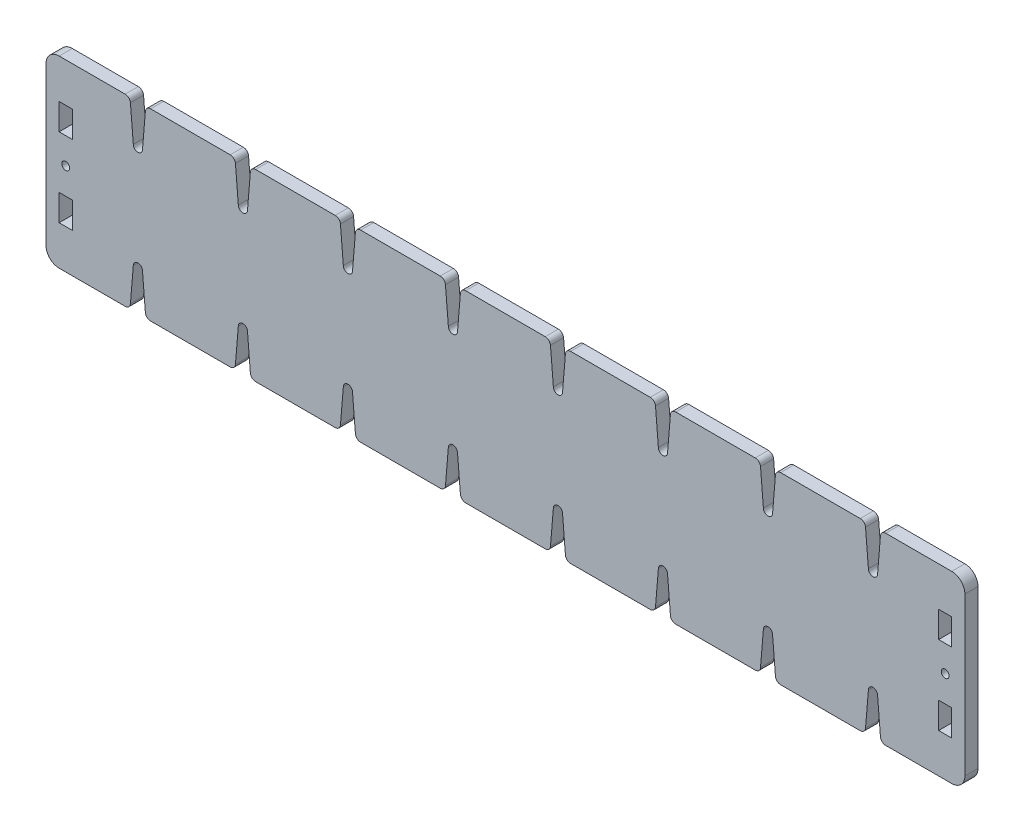
SolidWorks part; units mm, degrees
ref_plane "Front Plane" through (0, 0, 0) normal (0, 0, 1) x (1, 0, 0)
ref_plane "Top Plane" through (0, 0, 0) normal (0, 1, 0) x (1, 0, 0)
ref_plane "Right Plane" through (0, 0, 0) normal (1, 0, 0) x (0, 0, -1)
sketch "Sketch1" plane through (0, 0, 0) normal (0, 0, 1) x (1, 0, 0)
  line L0 (-90.218, 10) -> (299.3045, 10) construction
  line L1 (-85.8133, 35) -> (264.1867, 35)
  line L2 (-85.8133, 35) -> (-85.8133, -35)
  line L3 (-85.8133, -35) -> (264.1867, -35)
  line L4 (264.1867, 35) -> (264.1867, -35)
  line L5 (-80.8133, -10) -> (-75.8133, -10)
  line L6 (-91.3268, 0) -> (299.3045, 0) construction
  line L7 (-80.8133, 20) -> (-75.8133, 20)
  line L8 (-80.8133, 20) -> (-80.8133, 10)
  line L9 (-80.8133, 10) -> (-75.8133, 10)
  line L10 (-75.8133, 20) -> (-75.8133, 10)
  line L11 (-75.8133, -20) -> (-75.8133, -10)
  line L12 (-80.8133, -20) -> (-75.8133, -20)
  line L13 (-80.8133, -20) -> (-80.8133, -10)
  line L14 (89.1867, 30.0157) -> (89.1867, -45.8134) construction
  line L15 (-78.3133, 24.0051) -> (-78.3133, -32.23) construction
  line L16 (259.1867, -20) -> (259.1867, -10)
  line L17 (259.1867, -20) -> (254.1867, -20)
  line L18 (254.1867, -20) -> (254.1867, -10)
  line L19 (259.1867, -10) -> (254.1867, -10)
  line L20 (259.1867, 10) -> (254.1867, 10)
  line L21 (254.1867, 20) -> (254.1867, 10)
  line L22 (259.1867, 20) -> (254.1867, 20)
  line L23 (259.1867, 20) -> (259.1867, 10)
  circle A31 centre (-78.3133, 0) radius 1.5
  circle A32 centre (256.6867, 0) radius 1.5
  point P6 (89.1867, -35)
  point P13 (-85.8133, 0)
  point P82 (-78.3133, 20)
  dimension "D1" = 70
  dimension "D2" = 350
  dimension "D3" = 20
  dimension "D4" = 10
  dimension "D7" = 5
  dimension "D8" = 5
extrude "Boss-Extrude1" add sketch "Sketch1" along normal blind 5
sketch "Sketch2" plane through (0, 0, 5) normal (0, 0, 1) x (1, 0, 0)
  line L0 (-50.8133, 26.1544) -> (-50.8133, -32.4929) construction
  line L1 (-85.8133, 35) -> (-85.8133, -35) construction
  line L2 (264.1867, 35) -> (-85.8133, 35) construction
  line L3 (-53.8133, 35) -> (-47.8133, 35)
  line L4 (-53.8133, 35) -> (-52.5633, 20)
  line L6 (-47.8133, 35) -> (-49.0633, 20)
  line L7 (-86.9763, 0) -> (351.4175, 0) construction
  line L8 (-13.8133, 35) -> (-7.8133, 35)
  line L9 (-13.8133, 35) -> (-12.5633, 20)
  line L10 (-7.8133, 35) -> (-9.0633, 20)
  line L11 (26.1867, 35) -> (32.1867, 35)
  line L12 (26.1867, 35) -> (27.4367, 20)
  line L13 (32.1867, 35) -> (30.9367, 20)
  line L14 (66.1867, 35) -> (72.1867, 35)
  line L15 (66.1867, 35) -> (67.4367, 20)
  line L16 (72.1867, 35) -> (70.9367, 20)
  line L17 (106.1867, 35) -> (112.1867, 35)
  line L18 (106.1867, 35) -> (107.4367, 20)
  line L19 (112.1867, 35) -> (110.9367, 20)
  line L20 (146.1867, 35) -> (152.1867, 35)
  line L21 (146.1867, 35) -> (147.4367, 20)
  line L22 (152.1867, 35) -> (150.9367, 20)
  line L23 (186.1867, 35) -> (192.1867, 35)
  line L24 (186.1867, 35) -> (187.4367, 20)
  line L25 (192.1867, 35) -> (190.9367, 20)
  line L26 (226.1867, 35) -> (232.1867, 35)
  line L27 (226.1867, 35) -> (227.4367, 20)
  line L28 (232.1867, 35) -> (230.9367, 20)
  line L71 (232.1867, -35) -> (230.9367, -20)
  line L72 (226.1867, -35) -> (227.4367, -20)
  line L73 (226.1867, -35) -> (232.1867, -35)
  line L74 (192.1867, -35) -> (190.9367, -20)
  line L75 (186.1867, -35) -> (187.4367, -20)
  line L76 (186.1867, -35) -> (192.1867, -35)
  line L77 (152.1867, -35) -> (150.9367, -20)
  line L78 (146.1867, -35) -> (147.4367, -20)
  line L79 (146.1867, -35) -> (152.1867, -35)
  line L80 (112.1867, -35) -> (110.9367, -20)
  line L81 (106.1867, -35) -> (107.4367, -20)
  line L82 (106.1867, -35) -> (112.1867, -35)
  line L83 (72.1867, -35) -> (70.9367, -20)
  line L84 (66.1867, -35) -> (67.4367, -20)
  line L85 (66.1867, -35) -> (72.1867, -35)
  line L86 (32.1867, -35) -> (30.9367, -20)
  line L87 (26.1867, -35) -> (27.4367, -20)
  line L88 (26.1867, -35) -> (32.1867, -35)
  line L89 (-7.8133, -35) -> (-9.0633, -20)
  line L90 (-13.8133, -35) -> (-12.5633, -20)
  line L91 (-13.8133, -35) -> (-7.8133, -35)
  line L92 (-47.8133, -35) -> (-49.0633, -20)
  line L93 (-53.8133, -35) -> (-52.5633, -20)
  line L94 (-53.8133, -35) -> (-47.8133, -35)
  line L95 (-54.6736, 20) -> (-41.4603, 20) construction
  line L99 (264.1867, 35) -> (-85.8133, 35) construction
  arc A0 (-52.5633, 20) -> (-49.0633, 20) centre (-50.8133, 20) ccw
  arc A1 (-12.5633, 20) -> (-9.0633, 20) centre (-10.8133, 20) ccw
  arc A2 (27.4367, 20) -> (30.9367, 20) centre (29.1867, 20) ccw
  arc A3 (67.4367, 20) -> (70.9367, 20) centre (69.1867, 20) ccw
  arc A4 (107.4367, 20) -> (110.9367, 20) centre (109.1867, 20) ccw
  arc A5 (147.4367, 20) -> (150.9367, 20) centre (149.1867, 20) ccw
  arc A6 (187.4367, 20) -> (190.9367, 20) centre (189.1867, 20) ccw
  arc A7 (227.4367, 20) -> (230.9367, 20) centre (229.1867, 20) ccw
  arc A22 (227.4367, -20) -> (230.9367, -20) centre (229.1867, -20) cw
  arc A23 (187.4367, -20) -> (190.9367, -20) centre (189.1867, -20) cw
  arc A24 (147.4367, -20) -> (150.9367, -20) centre (149.1867, -20) cw
  arc A25 (107.4367, -20) -> (110.9367, -20) centre (109.1867, -20) cw
  arc A26 (67.4367, -20) -> (70.9367, -20) centre (69.1867, -20) cw
  arc A27 (27.4367, -20) -> (30.9367, -20) centre (29.1867, -20) cw
  arc A28 (-12.5633, -20) -> (-9.0633, -20) centre (-10.8133, -20) cw
  arc A29 (-52.5633, -20) -> (-49.0633, -20) centre (-50.8133, -20) cw
  circle A31 centre (-50.8133, 20) radius 17.5 construction
  circle A32 centre (-10.8133, 20) radius 17.5 construction
  circle A33 centre (29.1867, 20) radius 17.5 construction
  circle A34 centre (69.1867, 20) radius 17.5 construction
  circle A35 centre (109.1867, 20) radius 17.5 construction
  circle A36 centre (149.1867, 20) radius 17.5 construction
  circle A37 centre (189.1867, 20) radius 17.5 construction
  circle A38 centre (229.1867, 20) radius 17.5 construction
  point P10 (-50.8133, 35)
  point P23 (0, 0)
  dimension "D1" = 35
  dimension "D2" = 6
  dimension "D3" = 8
  dimension "D4" = 3.5
  dimension "D6" = 15
extrude "Cut-Extrude1" cut sketch "Sketch2" against normal blind 5
fillet "Fillet1" radius 2 32 edges at (-47.8133, -35, 2.5) (-53.8133, -35, 2.5) (-7.8133, -35, 2.5) (-13.8133, -35, 2.5) (32.1867, -35, 2.5) (26.1867, -35, 2.5) (72.1867, -35, 2.5) (66.1867, -35, 2.5) (112.1867, -35, 2.5) (106.1867, -35, 2.5) (152.1867, -35, 2.5) (146.1867, -35, 2.5) (192.1867, -35, 2.5) (186.1867, -35, 2.5) (226.1867, -35, 2.5) (232.1867, -35, 2.5) (232.1867, 35, 2.5) (226.1867, 35, 2.5) (192.1867, 35, 2.5) (186.1867, 35, 2.5) (152.1867, 35, 2.5) (112.1867, 35, 2.5) (146.1867, 35, 2.5) (106.1867, 35, 2.5) (72.1867, 35, 2.5) (66.1867, 35, 2.5) (32.1867, 35, 2.5) (26.1867, 35, 2.5) (-7.8133, 35, 2.5) (-13.8133, 35, 2.5) (-53.8133, 35, 2.5) (-47.8133, 35, 2.5)
fillet "Congé1" radius 5 4 edges at (-85.8133, -35, 2.5) (-85.8133, 35, 2.5) (264.1867, -35, 2.5) (264.1867, 35, 2.5)
